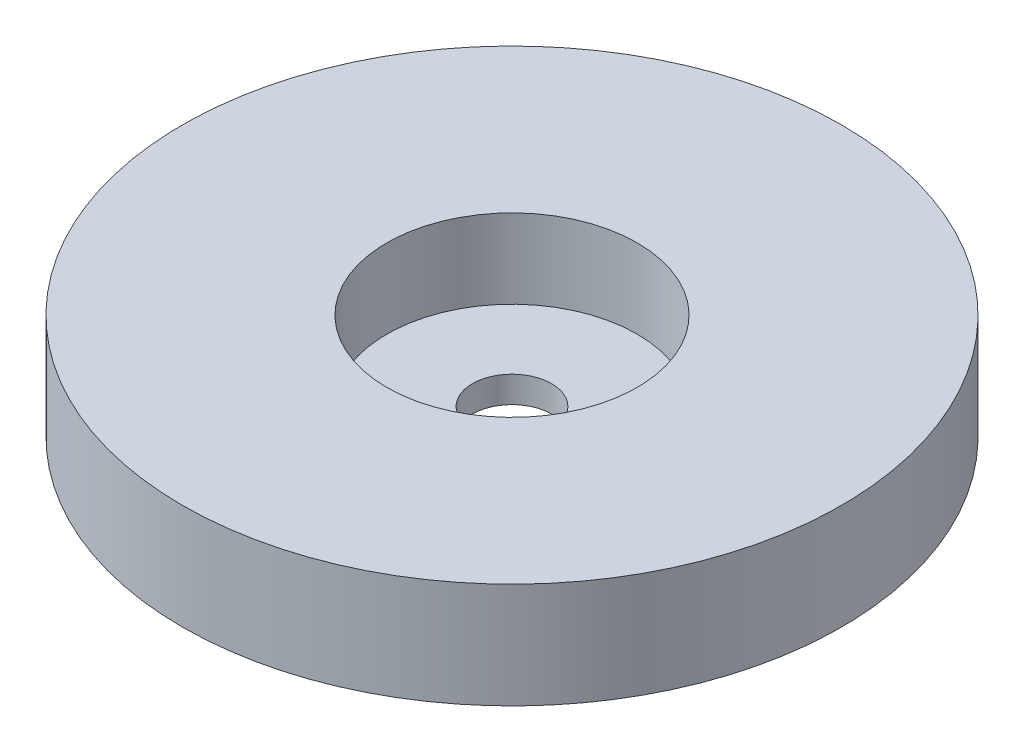
SolidWorks part; units mm, degrees
ref_plane "Plan de face" through (0, 0, 0) normal (0, 0, 1) x (1, 0, 0)
ref_plane "Plan de dessus" through (0, 0, 0) normal (0, 1, 0) x (1, 0, 0)
ref_plane "Plan de droite" through (0, 0, 0) normal (1, 0, 0) x (0, 0, -1)
sketch "Esquisse1" plane through (0, 0, 0) normal (0, 1, 0) x (1, 0, 0)
  circle A0 centre (0, 0) radius 25
  dimension "D1" = 50
extrude "Boss.-Extru.1" add sketch "Esquisse1" along normal blind 8
sketch "Esquisse2" plane through (0, 8, 0) normal (0, 1, 0) x (1, 0, 0)
  circle A0 centre (0, 0) radius 9.5
  dimension "D1" = 19
extrude "Enlèv. mat.-Extru.1" cut sketch "Esquisse2" against normal blind 6
sketch "Esquisse4" plane through (0, 0, 0) normal (0, -1, 0) x (1, 0, 0)
  circle A0 centre (0, 0) radius 3
  dimension "D1" = 6
extrude "Enlèv. mat.-Extru.2" cut sketch "Esquisse4" against normal through all both and the other way through all
